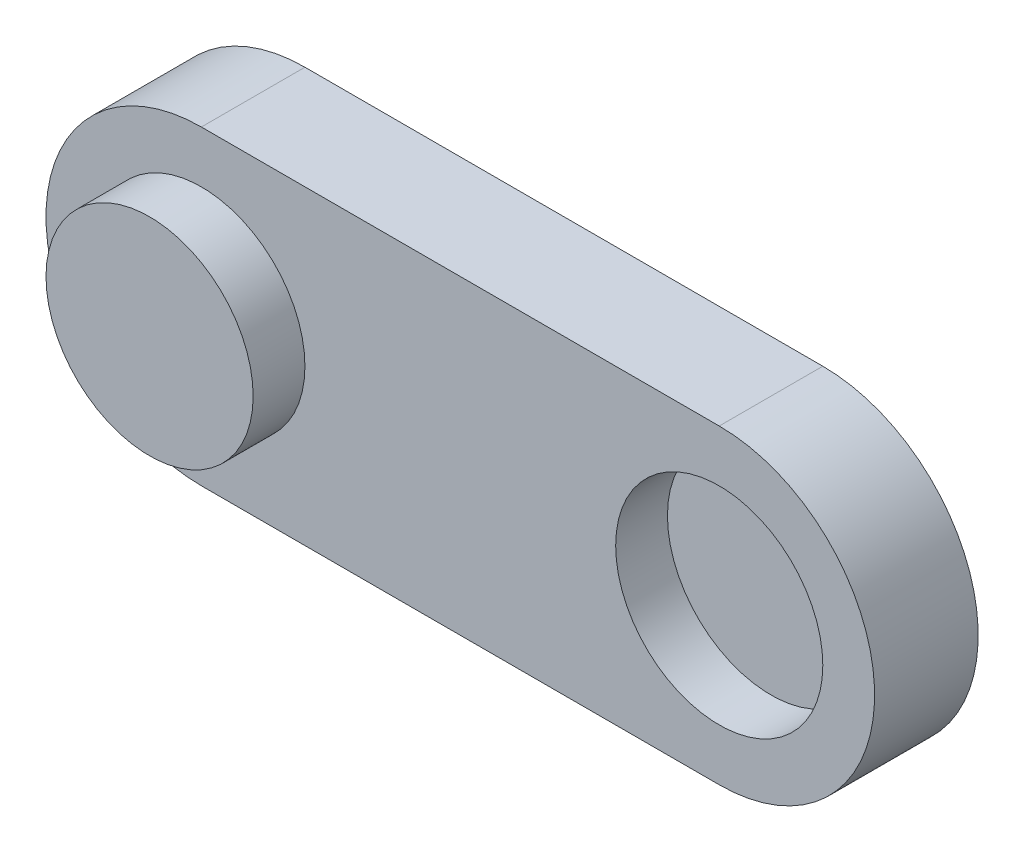
SolidWorks part; units mm, degrees
ref_plane "Alzado" through (0, 0, 0) normal (0, 0, 1) x (1, 0, 0)
ref_plane "Planta" through (0, 0, 0) normal (0, 1, 0) x (1, 0, 0)
ref_plane "Vista lateral" through (0, 0, 0) normal (1, 0, 0) x (0, 0, -1)
sketch "Croquis1" plane through (0, 0, 0) normal (0, 0, 1) x (1, 0, 0)
  line L0 (0, 0) -> (100, 0) construction
  line L1 (0, 30) -> (100, 30)
  line L2 (0, -30) -> (100, -30)
  arc A0 (0, 30) -> (0, -30) centre (0, 0) ccw
  arc A1 (100, -30) -> (100, 30) centre (100, 0) ccw
  point P3 (50, 0)
  dimension "D1" = 100
  dimension "D2" = 60
extrude "Saliente-Extruir1" add sketch "Croquis1" along normal blind 20
sketch "Croquis2" plane through (0, 0, 20) normal (0, 0, 1) x (1, 0, 0)
  circle A0 centre (0, 0) radius 20
  dimension "D1" = 40
extrude "Saliente-Extruir2" add sketch "Croquis2" along normal blind 10
sketch "Croquis3" plane through (0, 0, 20) normal (0, 0, 1) x (1, 0, 0)
  circle A0 centre (100, 0) radius 20
  dimension "D1" = 40
  dimension "D2" = 0
  dimension "D3" = 30
extrude "Cortar-Extruir1" cut sketch "Croquis3" against normal blind 10
